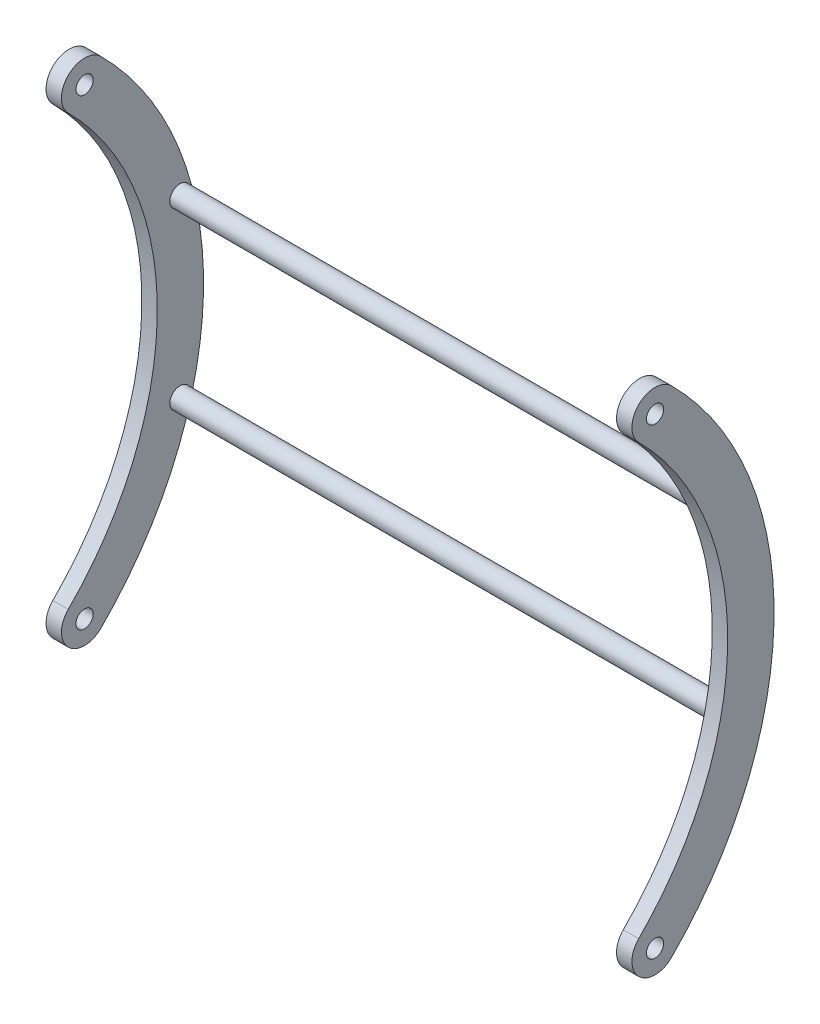
SolidWorks part; units mm, degrees
material "ABS"
ref_plane "Front Plane" through (0, 0, 0) normal (0, 0, 1) x (1, 0, 0)
ref_plane "Top Plane" through (0, 0, 0) normal (0, 1, 0) x (1, 0, 0)
ref_plane "Right Plane" through (0, 0, 0) normal (1, 0, 0) x (0, 0, -1)
sketch "Sketch1" plane through (0, 0, 0) normal (1, 0, 0) x (0, 0, -1)
  circle A0 centre (-12.4526, -43.8806) radius 1.68
  circle A1 centre (-12.4526, 46.1194) radius 1.68
  arc A2 (-15.6346, -40.6986) -> (-9.2731, -47.065) centre (-12.4526, -43.8806) ccw
  arc A3 (-9.2731, 49.3039) -> (-15.6346, 42.9375) centre (-12.4526, 46.1194) ccw
  arc A4 (-9.2731, 49.3039) -> (-9.2731, -47.065) centre (-57.3821, 1.1194) cw
  arc A5 (-15.6346, -40.6986) -> (-15.6346, 42.9375) centre (-57.4526, 1.1194) ccw
extrude "Boss-Extrude1" add sketch "Sketch1" along normal blind 3 contours A5 A3 A4 A2
sketch "Sketch2" plane through (0, 0, 0) normal (-1, 0, 0) x (0, 0, 1)
  circle A5 centre (-6.1186, 18.1578) radius 2
  circle A6 centre (-6.1186, -15.8751) radius 2
  point P3 (-6.0304, 18.1599)
sketch "Sketch4" plane through (3, 0, 0) normal (1, 0, 0) x (0, 0, -1)
  circle A0 centre (-12.4539, 46.1207) radius 1.68
  circle A1 centre (-12.4539, -43.8818) radius 1.68
extrude "Cut-Extrude1" cut sketch "Sketch4" against normal through all
extrude "Boss-Extrude11" add sketch "Sketch2" along normal blind 108
sketch "Sketch8" plane through (-108, 0, 0) normal (-1, 0, 0) x (0, 0, 1)
  arc A0 (9.2731, 49.3039) -> (15.6346, 42.9375) centre (12.4539, 46.1207) cw
  arc A1 (9.2731, -47.065) -> (15.6346, -40.6986) centre (12.4539, -43.8818) ccw
  circle A2 centre (12.4539, 46.1207) radius 1.68
  circle A3 centre (12.4539, -43.8818) radius 1.68
  arc A4 (9.2731, 49.3039) -> (9.2731, -47.065) centre (57.4198, 1.1194) ccw
  arc A5 (15.6346, -40.6986) -> (15.6346, 42.9375) centre (57.4198, 1.1194) cw
extrude "Boss-Extrude12" add sketch "Sketch8" along normal blind 3
